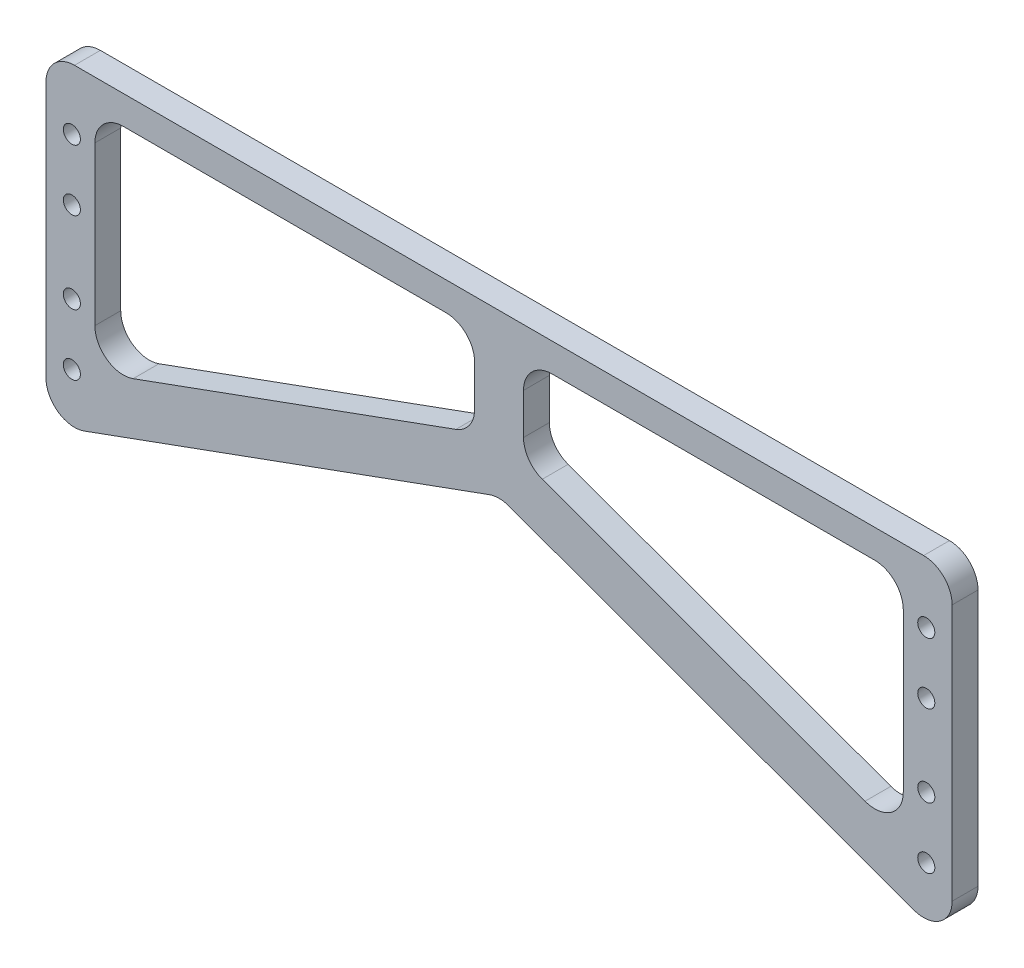
SolidWorks part; units mm, degrees
ref_plane "Front Plane" through (0, 0, 0) normal (0, 0, 1) x (1, 0, 0)
ref_plane "Top Plane" through (0, 0, 0) normal (0, 1, 0) x (1, 0, 0)
ref_plane "Right Plane" through (0, 0, 0) normal (1, 0, 0) x (0, 0, -1)
sketch "Sketch1" plane through (0, 0, 0) normal (0, 0, 1) x (1, 0, 0)
  line L1 (-111.25, -40) -> (111.25, -40)
  line L2 (-111.25, -40) -> (-111.25, 40)
  line L3 (-111.25, 40) -> (111.25, 40)
  line L4 (111.25, -40) -> (111.25, 40)
  line L5 (-111.25, -40) -> (111.25, 40) construction
  line L6 (-111.25, 40) -> (111.25, -40) construction
  point P0 (0, 0)
  dimension "D1" = 222.5
  dimension "D2" = 80
extrude "Boss-Extrude1" add sketch "Sketch1" along normal blind 6.35
sketch "Sketch2" plane through (0, 0, 6.35) normal (0, 0, 1) x (1, 0, 0)
  line L0 (111.25, -40) -> (0, 0.4917)
  line L1 (0, 0.4917) -> (-111.25, -40)
  line L2 (-111.25, -40) -> (111.25, -40)
  line L3 (0, 40) -> (0, -40) construction
  line L4 (111.25, 40) -> (-111.25, 40) construction
  dimension "D1" = 20
extrude "Cut-Extrude1" cut sketch "Sketch2" against normal through all
sketch "Sketch3" plane through (0, 0, 6.35) normal (0, 0, 1) x (1, 0, 0)
  line L0 (-99.25, 33) -> (-99.25, -22.8622)
  line L1 (-99.25, -22.8622) -> (-6, 11.078)
  line L2 (-6, 11.078) -> (-6, 33)
  line L3 (-6, 33) -> (-99.25, 33)
  line L4 (0, 0.4917) -> (0, 56.2405) construction
  line L5 (111.25, -40) -> (111.25, 40) construction
  line L7 (111.25, 40) -> (-111.25, 40) construction
  line L8 (-111.25, 40) -> (-111.25, -40) construction
  line L9 (0, 0.4917) -> (-111.25, -40) construction
  dimension "D1" = 12
  dimension "D2" = 12
  dimension "D3" = 7
  dimension "D4" = 12
extrude "Cut-Extrude2" cut sketch "Sketch3" against normal through all
hole_wizard "M5x0.8 Tapped Hole1" positions "Sketch5" profile "Sketch4" tap size "M5x0.8" standard "ANSI Metric"
sketch "Sketch5" plane through (0, 0, 0) normal (0, 0, -1) x (-1, 0, 0)
  line L0 (104.9, 40) -> (104.9, -49.7544) construction
  line L1 (-111.25, 40) -> (111.25, 40) construction
  line L6 (111.25, 40) -> (111.25, -40) construction
  point P23 (104.9, -25)
  point P25 (104.9, -10)
  point P27 (104.9, 25)
  point P29 (104.9, 10)
  point P34 (106.7945, 20.0583)
  dimension "D1" = 6.35
  dimension "D2" = 15
  dimension "D3" = 15
  dimension "D4" = 15
  dimension "D5" = 15
sketch "Sketch4" plane through (-104.9, -25, 0) normal (1, 0, 0) x (0, 1, 0)
  line L0 (0, 0) -> (0, 13.6618)
  line L1 (0, 13.6618) -> (2.1, 12.4)
  line L2 (2.1, 12.4) -> (2.1, 0)
  line L5 (2.1, 0) -> (0, 0)
  line L10 (0, 13.6618) -> (-2.1, 12.4) construction
  line L11 (0, -6.35) -> (0, 107.95) construction
  dimension "Tap Drill Dia." = 4.2
  dimension "Tap Drill Depth" = 12.4
  dimension "Drill Angle" = 118
cosmetic thread "Hole Thread1" parameters "D1"=6.35, "D2"=5
cosmetic thread "Hole Thread2" parameters "D1"=6.35, "D2"=5
cosmetic thread "Hole Thread3" parameters "D1"=6.35, "D2"=5
cosmetic thread "Hole Thread4" parameters "D1"=6.35, "D2"=5
mirror "Mirror1" about plane through (0, 0, 0) normal (1, 0, 0) of "M5x0.8 Tapped Hole1", "Cut-Extrude2"
fillet "Fillet1" radius 7 13 edges at (6, 11.078, 3.175) (99.25, -22.8622, 3.175) (-6, 11.078, 3.175) (-6, 33, 3.175) (99.25, 33, 3.175) (6, 33, 3.175) (-99.25, 33, 3.175) (111.25, 40, 3.175) (111.25, -40, 3.175) (0, 0.4917, 3.175) (-111.25, -40, 3.175) (-111.25, 40, 3.175) (-99.25, -22.8622, 3.175)
